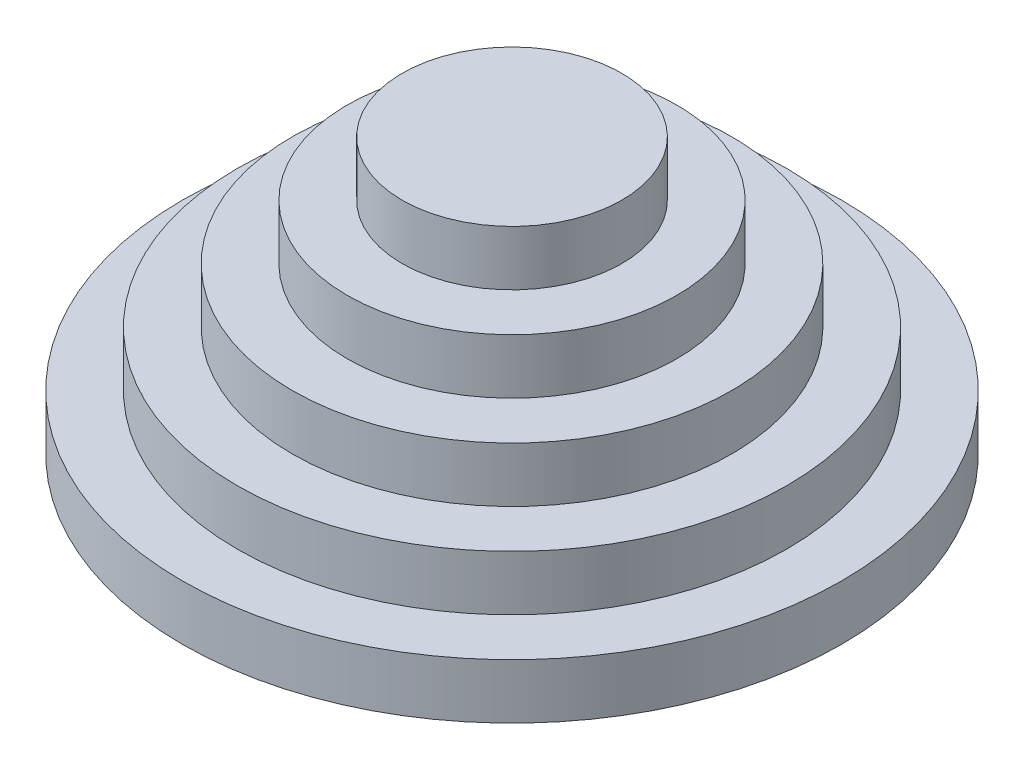
SolidWorks part; units mm, degrees
ref_plane "Piano frontale" through (0, 0, 0) normal (0, 0, 1) x (1, 0, 0)
ref_plane "Piano superiore" through (0, 0, 0) normal (0, 1, 0) x (1, 0, 0)
ref_plane "Piano destro" through (0, 0, 0) normal (1, 0, 0) x (0, 0, -1)
sketch "Schizzo1" plane through (0, 0, 0) normal (0, 1, 0) x (1, 0, 0)
  circle A0 centre (0, 0) radius 25
  dimension "D1" = 50
extrude "Estrusione-Estrusione1" add sketch "Schizzo1" along normal blind 5
sketch "Schizzo2" plane through (0, 5, 0) normal (0, 1, 0) x (1, 0, 0)
  circle A0 centre (0, 0) radius 20
  dimension "D1" = 40
extrude "Estrusione-Estrusione2" add sketch "Schizzo2" along normal blind 5
sketch "Schizzo3" plane through (0, 10, 0) normal (0, 1, 0) x (1, 0, 0)
  circle A0 centre (0, 0) radius 15
  dimension "D1" = 30
extrude "Estrusione-Estrusione3" add sketch "Schizzo3" along normal blind 5
sketch "Schizzo4" plane through (0, 15, 0) normal (0, 1, 0) x (1, 0, 0)
  circle A0 centre (0, 0) radius 10
  dimension "D1" = 20
extrude "Estrusione-Estrusione4" add sketch "Schizzo4" along normal blind 5
sketch "Schizzo6" plane through (0, 0, 0) normal (0, -1, 0) x (1, 0, 0)
  circle A0 centre (0, 0) radius 30
  dimension "D1" = 60
extrude "Estrusione-Estrusione6" add sketch "Schizzo6" along normal blind 5
